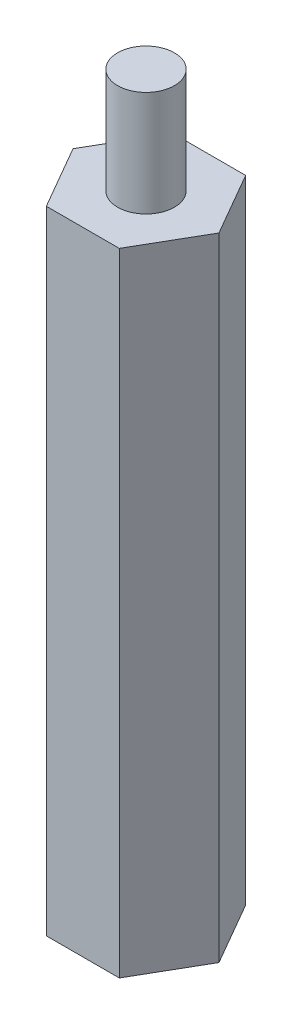
SolidWorks part; units mm, degrees
ref_plane "정면도" through (0, 0, 0) normal (0, 0, 1) x (1, 0, 0)
ref_plane "평면도" through (0, 0, 0) normal (0, 1, 0) x (1, 0, 0)
ref_plane "우측면도" through (0, 0, 0) normal (1, 0, 0) x (0, 0, -1)
sketch "스케치1" plane through (0, 0, 0) normal (0, 1, 0) x (1, 0, 0)
  line L1 (3.4641, 0) -> (1.7321, 3)
  line L2 (1.7321, 3) -> (-1.7321, 3)
  line L3 (-1.7321, 3) -> (-3.4641, 0)
  line L4 (-3.4641, 0) -> (-1.7321, -3)
  line L5 (-1.7321, -3) -> (1.7321, -3)
  line L6 (1.7321, -3) -> (3.4641, 0)
  circle A0 centre (0, 0) radius 3 construction
  dimension "D1" = 6
extrude "보스-돌출1" add sketch "스케치1" along normal blind 30
sketch "스케치2" plane through (0, 30, 0) normal (0, 1, 0) x (1, 0, 0)
  circle A0 centre (0, 0) radius 1.35
  dimension "D1" = 2.7
extrude "보스-돌출2" add sketch "스케치2" along normal blind 5
sketch "스케치3" plane through (0, 0, 0) normal (0, -1, 0) x (1, 0, 0)
  circle A0 centre (0, 0) radius 1.35
  dimension "D1" = 2.7
extrude "컷-돌출1" cut sketch "스케치3" against normal blind 6
